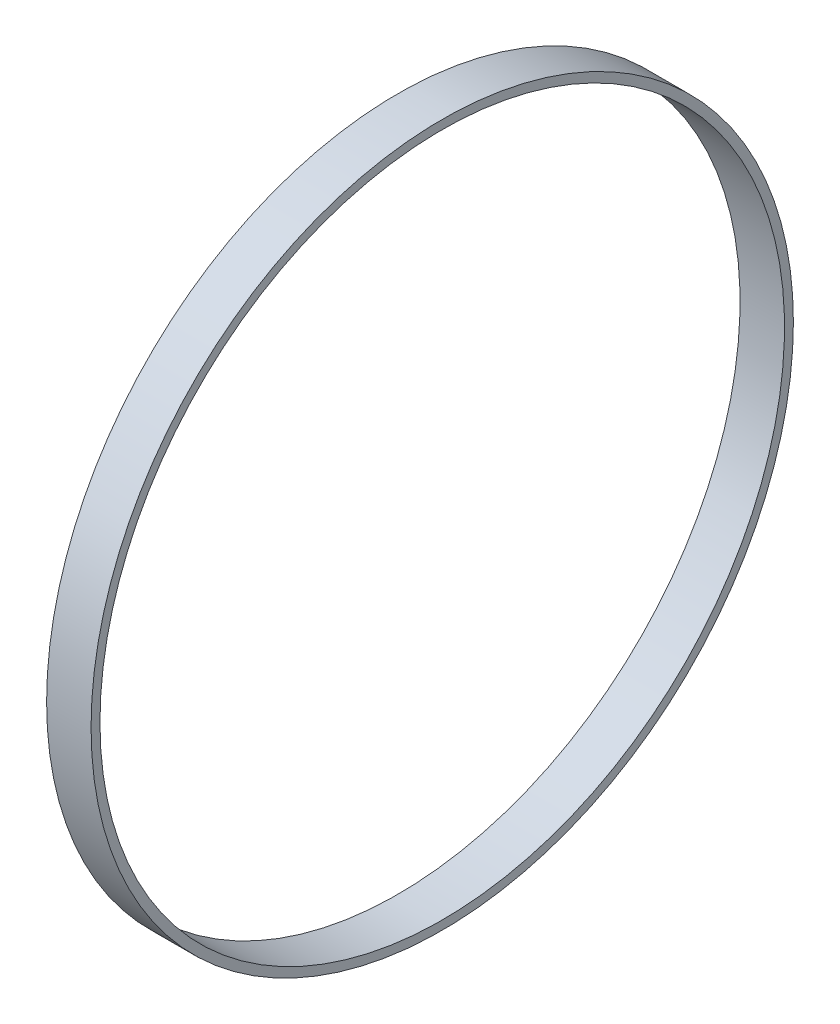
SolidWorks part; units mm, degrees
material "Silicon Rubber"
ref_plane "Front Plane" through (0, 0, 0) normal (0, 0, 1) x (1, 0, 0)
ref_plane "Top Plane" through (0, 0, 0) normal (0, 1, 0) x (1, 0, 0)
ref_plane "Right Plane" through (0, 0, 0) normal (1, 0, 0) x (0, 0, -1)
sketch "Sketch1" plane through (0, 0, 0) normal (0, 1, 0) x (1, 0, 0)
  line L0 (0, -5) -> (0, -390) construction
  line L1 (-25, -5) -> (25, -5)
  line L2 (-25, -5) -> (-25, 5)
  line L3 (-25, 5) -> (25, 5)
  line L4 (25, -5) -> (25, 5)
  line L5 (-25, -5) -> (25, 5) construction
  line L6 (-25, 5) -> (25, -5) construction
  line L7 (-20.7823, -390) -> (25, -390) construction
  point P0 (0, 0)
revolve "Revolve1" add sketch "Sketch1" angle 360 about L7
